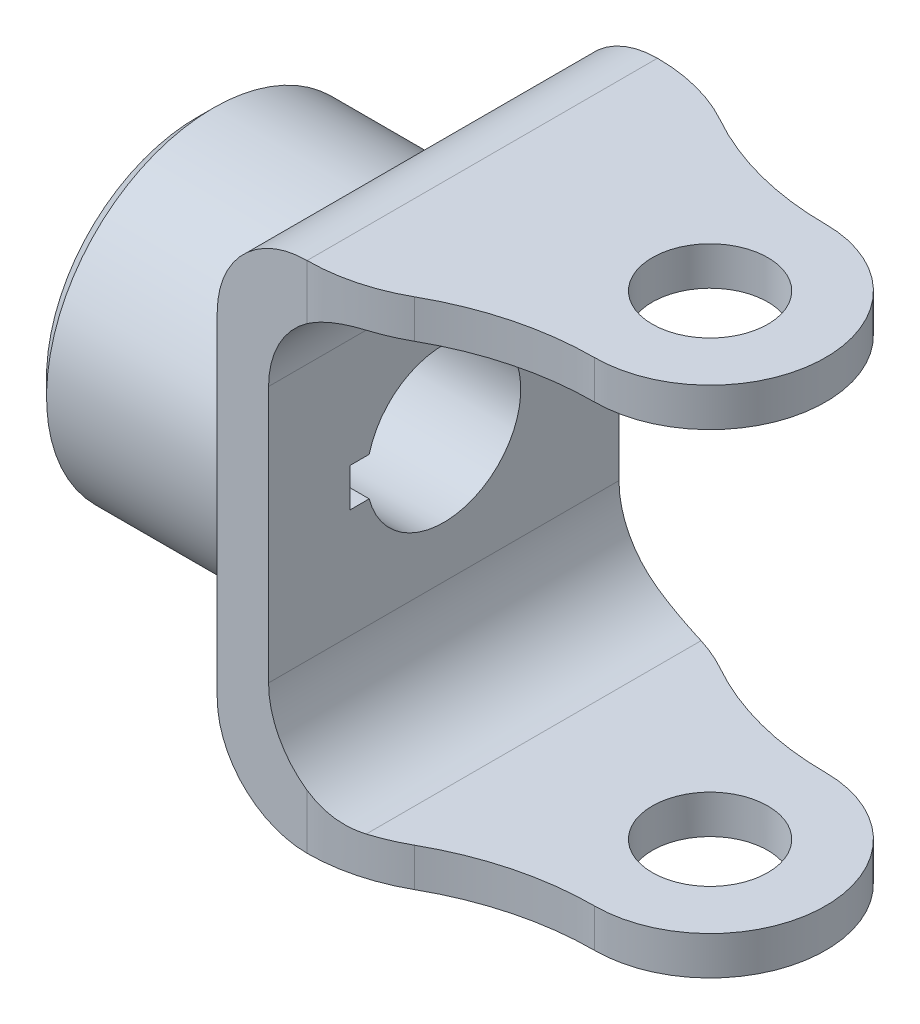
SolidWorks part; units mm, degrees
ref_plane "Front Plane" through (0, 0, 0) normal (0, 0, 1) x (1, 0, 0)
ref_plane "Top Plane" through (0, 0, 0) normal (0, 1, 0) x (1, 0, 0)
ref_plane "Right Plane" through (0, 0, 0) normal (1, 0, 0) x (0, 0, -1)
sketch "Sketch0" plane through (0, 0, 0) normal (0, 1, 0) x (1, 0, 0)
  line L0 (-63.5, 0) -> (63.5, 0) construction
  line L1 (-63.5, 20.6375) -> (-63.5, -20.6375) construction
  line L2 (-32.9406, 9.525) -> (-32.9406, -9.525) construction
  line L3 (-32.9406, 9.525) -> (-23.4156, 0) construction
  line L4 (-23.4156, 0) -> (-32.9406, -9.525) construction
  line L5 (-28.1781, 4.7625) -> (-28.1781, -4.7625) construction
  line L6 (0, 31.75) -> (0, -31.75) construction
  point P7 (-32.9406, 0)
  point P8 (0, 0)
  point P12 (-28.1781, 0)
  dimension "Overall Width" = 63.5
  dimension "Shaft Dia" = 19.05
sketch "Sketch1" plane through (0, 0, 0) normal (0, 1, 0) x (1, 0, 0)
  line L0 (-63.5, 20.6375) -> (-32.9406, 20.6375)
  line L2 (-32.9406, 0) -> (-63.5, 0)
  line L3 (-63.5, 0) -> (-63.5, 20.6375)
  line L4 (-63.5, 20.6375) -> (-63.5, -20.6375) construction
  line L5 (-63.5, 0) -> (63.5, 0) construction
  line L9 (-32.9406, 20.6375) -> (-32.9406, 0)
  line L11 (0, 0) -> (20.6375, 0) construction
  line L14 (0, 31.75) -> (0, 0) construction
  circle A0 centre (0, 0) radius 20.6375 construction
revolve "Revolve1" add sketch "Sketch1" angle 360 about L0
sketch "Sketch30" plane through (0, 0, 0) normal (0, 1, 0) x (1, 0, 0)
  line L0 (-39.2906, 21.6694) -> (-39.2906, -21.6694)
  line L1 (-39.2906, -21.6694) -> (-21.8281, -21.6694)
  line L2 (-39.2906, 21.6694) -> (-21.8281, 21.6694)
  line L3 (0, 14.2875) -> (-25.0022, 14.2875) construction
  line L4 (0, -14.2875) -> (-25.0022, -14.2875) construction
  line L5 (-21.8281, 21.6694) -> (14.2875, 21.6694)
  line L6 (14.2875, 21.6694) -> (14.2875, -21.6694)
  line L7 (-21.8281, -21.6694) -> (14.2875, -21.6694)
  line L8 (0, 31.75) -> (0, -31.75) construction
  line L9 (9.525, 0) -> (14.2875, 0) construction
  circle A0 centre (0, 0) radius 9.525 construction
  arc A2 (0, -14.2875) -> (0, 14.2875) centre (0, 0) ccw construction
  arc A3 (0, 14.2875) -> (-21.8281, 21.6694) centre (0, 50.2512) cw construction
  arc A4 (0, -14.2875) -> (-21.8281, -21.6694) centre (0, -50.2512) ccw construction
  circle A5 centre (0, 0) radius 14.2875 construction
  point P5 (12.388, 3.7874)
  dimension "D2" = 19.05
  dimension "D1" = 43.3388
  dimension "D3" = 4.7625
  dimension "D4" = 6.35
  dimension "D5" = 17.4625
extrude "Boss-Extrude6" add sketch "Sketch30" along normal mid plane 63.5
chamfer "Chamfer1" distance 2.0638 angle 45 1 edges at (-63.5, 0, 20.6375)
sketch "Sketch3" plane through (0, 0, 0) normal (0, 0, 1) x (1, 0, 0)
  line L0 (-63.5, 0) -> (63.5, 0) construction
  line L1 (-32.9406, 0) -> (32.9406, 0) construction
  line L2 (-21.8281, 26.9875) -> (32.9406, 26.9875)
  line L3 (32.9406, 26.9875) -> (32.9406, -26.9875)
  line L4 (-21.8281, -26.9875) -> (32.9406, -26.9875)
  line L5 (-32.9406, 15.875) -> (-32.9406, -15.875)
  line L7 (-39.2906, 31.75) -> (14.2875, 31.75) construction
  line L8 (-39.2906, 31.75) -> (-39.2906, -31.75) construction
  line L9 (-39.2906, 31.75) -> (-28.1781, 31.75)
  line L10 (-39.2906, 31.75) -> (-39.2906, 20.6375)
  line L11 (-39.2906, -31.75) -> (-39.2906, -20.6375)
  line L12 (-39.2906, -31.75) -> (-28.1781, -31.75)
  arc A0 (-39.2906, 20.6375) -> (-28.1781, 31.75) centre (-28.1781, 20.6375) cw
  arc A1 (-32.9406, 15.875) -> (-21.8281, 26.9875) centre (-21.8281, 15.875) cw
  arc A2 (-32.9406, -15.875) -> (-21.8281, -26.9875) centre (-21.8281, -15.875) ccw
  arc A3 (-39.2906, -20.6375) -> (-28.1781, -31.75) centre (-28.1781, -20.6375) ccw
  dimension "D2" = 53.975
  dimension "D1" = 4.7625
  dimension "D4" = 17.4625
extrude "Extrude3" cut sketch "Sketch3" against normal through all and the other way through all
sketch "Sketch2" plane through (0, 0, 0) normal (0, 1, 0) x (1, 0, 0)
  line L0 (-52.3875, 20.6375) -> (-32.9406, 20.6375) construction
  line L1 (-21.8281, -21.6694) -> (-21.8281, -31.75) construction
  line L2 (-21.8281, 21.6694) -> (-21.8281, 31.75) construction
  line L3 (-32.9406, 9.525) -> (-32.9406, -9.525) construction
  line L4 (-63.5, 0) -> (14.2875, 0) construction
  line L6 (20.6375, 31.75) -> (20.6375, -31.75)
  line L8 (0, 14.2875) -> (0, 0) construction
  line L9 (-21.8281, 31.75) -> (20.6375, 31.75)
  line L10 (-32.9406, 20.6375) -> (-32.9406, -14.4138) construction
  line L11 (-39.2906, 21.6694) -> (-21.8281, 21.6694) construction
  line L12 (-21.8281, -31.75) -> (20.6375, -31.75)
  line L13 (-63.5, 20.6375) -> (-32.9406, 20.6375) construction
  line L14 (-28.1781, 21.6694) -> (-21.8281, 31.75)
  line L15 (-63.5, 0) -> (63.5, 0) construction
  line L16 (-21.8281, -31.75) -> (-28.1781, -21.6694)
  line L17 (-39.2906, -21.6694) -> (-21.8281, -21.6694) construction
  arc A0 (0, -14.2875) -> (-21.8281, -21.6694) centre (0, -50.2512) ccw construction
  arc A1 (0, -14.2875) -> (0, 14.2875) centre (0, 0) ccw construction
  arc A2 (-21.8281, 21.6694) -> (0, 14.2875) centre (0, 50.2512) ccw construction
  arc A3 (0, -14.2875) -> (-17.6328, -18.9068) centre (0, -50.2512) ccw
  arc A4 (0, -14.2875) -> (0, 14.2875) centre (0, 0) ccw
  arc A5 (-17.6328, 18.9068) -> (0, 14.2875) centre (0, 50.2512) ccw
  arc A6 (-28.1781, 21.6694) -> (-17.6328, 18.9068) centre (-28.1781, 0.1613) cw
  arc A7 (-28.1781, -21.6694) -> (-17.6328, -18.9068) centre (-28.1781, -0.1613) ccw
extrude "Extrude1" cut sketch "Sketch2" against normal through all and the other way through all
sketch "Sketch4" plane through (-63.5, 0, 0) normal (-1, 0, 0) x (0, 0, 1)
  circle A0 centre (0, 0) radius 9.525
  circle A1 centre (0, 0) radius 9.525 construction
  dimension "Max Bore Dia" = 19.05
extrude "Extrude4" cut sketch "Sketch4" against normal up to vertex (30.5594 mm away) up to point (-32.9406, 0, -9.525)
sketch "Sketch6" plane through (0, 0, 0) normal (0, 1, 0) x (1, 0, 0)
  line L0 (-63.5, 0) -> (63.5, 0) construction
  line L1 (14.2875, 0) -> (7.1437, 0) construction
  line L2 (7.1437, 0) -> (0, 0) construction
  line L3 (14.2875, 21.6694) -> (14.2875, -21.6694) construction
  circle A0 centre (0, 0) radius 7.1437
  dimension "D1" = 14.2875
extrude "Extrude6" cut sketch "Sketch6" against normal through all and the other way through all
sketch "Sketch33" plane through (-63.5, 0, 0) normal (-1, 0, 0) x (0, 0, 1)
  line L0 (0, 0) -> (9.2225, 0) construction
  line L1 (9.2225, 2.3813) -> (11.6038, 2.3813)
  line L2 (9.2225, 2.3813) -> (9.2225, -2.3813)
  line L3 (9.2225, -2.3813) -> (11.6038, -2.3813)
  line L4 (11.6038, 2.3813) -> (11.6038, -2.3813)
  circle A0 centre (0, 0) radius 9.525 construction
  dimension "D1" = 4.7625
  dimension "D2" = 2.3813
extrude "Cut-Extrude1" cut sketch "Sketch33" against normal through all
sketch "Sketch34" plane through (0, 0, 0) normal (0, 1, 0) x (1, 0, 0)
  line L0 (-39.2906, 0) -> (-63.5, 0) construction
  line L2 (-63.5, 18.5737) -> (-63.5, -18.5737) construction
  circle A0 centre (-51.3953, 0) radius 4.7625
  point P7 (-39.2906, 0)
  point P8 (-51.3953, 0)
  dimension "D1" = 9.525
extrude "Cut-Extrude2" cut sketch "Sketch34" against normal through all
ref_plane "Plane1" through (-51.3953, 0, 0) normal (1, 0, 0) x (0, 0, -1)
sketch "Sketch35" plane through (-51.3953, 0, 0) normal (1, 0, 0) x (0, 0, -1)
  line L0 (-3.9688, -9.525) -> (-4.7625, -10.3187)
  line L1 (0, -9.525) -> (-3.9688, -9.525)
  line L2 (0, -9.525) -> (0, -22.225) construction
  line L3 (0, -22.225) -> (-3.9687, -22.225)
  line L4 (-4.7625, -10.3187) -> (-4.7625, -21.4313)
  line L5 (-3.9687, -22.225) -> (-4.7625, -21.4313)
  line L6 (0, -9.525) -> (0, -22.225)
  arc A0 (-9.2225, -2.3813) -> (-9.2225, 2.3813) centre (0, 0) ccw construction
  point P1 (-4.7625, -22.225)
  point P3 (-4.7625, -9.525)
  dimension "D1" = 12.7
  dimension "D2" = 9.525
  dimension "D3" = 0.7938
  dimension "D4" = 45
  dimension "D5" = 0.7938
  dimension "D6" = 45
revolve "Revolve2" add sketch "Sketch35" angle 360 about L2
sketch "Sketch36" plane through (0, -22.225, 0) normal (0, -1, 0) x (1, 0, 0)
  line L1 (-51.3953, -2.7496) -> (-49.0141, -1.3748)
  line L2 (-49.0141, -1.3748) -> (-49.0141, 1.3748)
  line L3 (-49.0141, 1.3748) -> (-51.3953, 2.7496)
  line L4 (-51.3953, 2.7496) -> (-53.7766, 1.3748)
  line L5 (-53.7766, 1.3748) -> (-53.7766, -1.3748)
  line L6 (-53.7766, -1.3748) -> (-51.3953, -2.7496)
  circle A0 centre (-51.3953, 0) radius 2.3812 construction
  dimension "D1" = 4.7625
extrude "Cut-Extrude3" cut sketch "Sketch36" against normal blind 3.302
sketch "Sketch37" plane through (0, -22.225, 0) normal (0, -1, 0) x (1, 0, 0)
  circle A0 centre (-51.3953, 0) radius 2.7496
  circle A1 centre (-51.3953, 0) radius 3.9687 construction
extrude "Cut-Extrude4" cut sketch "Sketch37" against normal through all draft 45
equation "\"D2@Sketch3\" = \"D1@Sketch3\" / 4"
equation "\"D1@Chamfer1\" = \"OD@Sketch0\"/20"
equation "\"D2@Sketch3\" = \"Overall Width@Sketch0\"*.85"
equation "\"D1@Sketch30\" = \"OD@Sketch0\"*1.05"
equation "\"D1@Boss-Extrude6\" = \"Overall Width@Sketch0\""
equation "\"D5@Sketch30\" = \"D4@Sketch3\""
equation "\"D2@Sketch32\" = \"D1@Sketch10\"*1.3"
equation "\"D1@Boss-Extrude8\" = \"D1@Sketch10\"*1.5"
